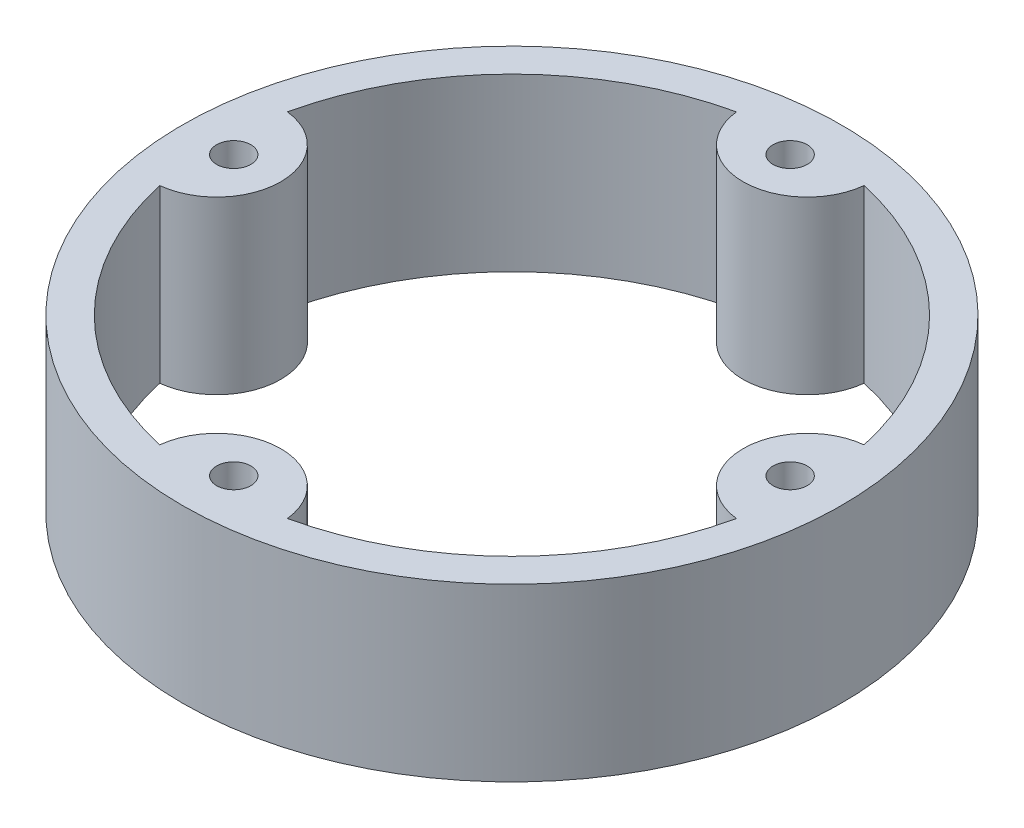
SolidWorks part; units mm, degrees
ref_plane "Ön Düzlem" through (0, 0, 0) normal (0, 0, 1) x (1, 0, 0)
ref_plane "Üst Düzlem" through (0, 0, 0) normal (0, 1, 0) x (1, 0, 0)
ref_plane "Sağ Düzlem" through (0, 0, 0) normal (1, 0, 0) x (0, 0, -1)
sketch "Çizim1" plane through (0, 0, 0) normal (0, 1, 0) x (1, 0, 0)
  circle A0 centre (0, 0) radius 38.5
  arc A1 (-33.6848, -7.4556) -> (-7.4556, -33.6848) centre (0, 0) ccw
  circle A2 centre (0, 32.5) radius 2
  circle A3 centre (32.5, 0) radius 2
  circle A4 centre (0, -32.5) radius 2
  circle A5 centre (-32.5, 0) radius 2
  arc A7 (-33.6848, -7.4556) -> (-33.6848, 7.4556) centre (-34.5, 0) ccw
  arc A8 (-7.4556, 33.6848) -> (7.4556, 33.6848) centre (0, 34.5) ccw
  arc A9 (33.6848, 7.4556) -> (33.6848, -7.4556) centre (34.5, 0) ccw
  arc A10 (7.4556, -33.6848) -> (-7.4556, -33.6848) centre (0, -34.5) ccw
  arc A11 (-7.4556, 33.6848) -> (-33.6848, 7.4556) centre (0, 0) ccw
  arc A12 (33.6848, 7.4556) -> (7.4556, 33.6848) centre (0, 0) ccw
  arc A13 (7.4556, -33.6848) -> (33.6848, -7.4556) centre (0, 0) ccw
  dimension "D1" = 4
  dimension "D2" = 4
extrude "Yükseklik-Ekstrüzyon1" add sketch "Çizim1" along normal blind 20
